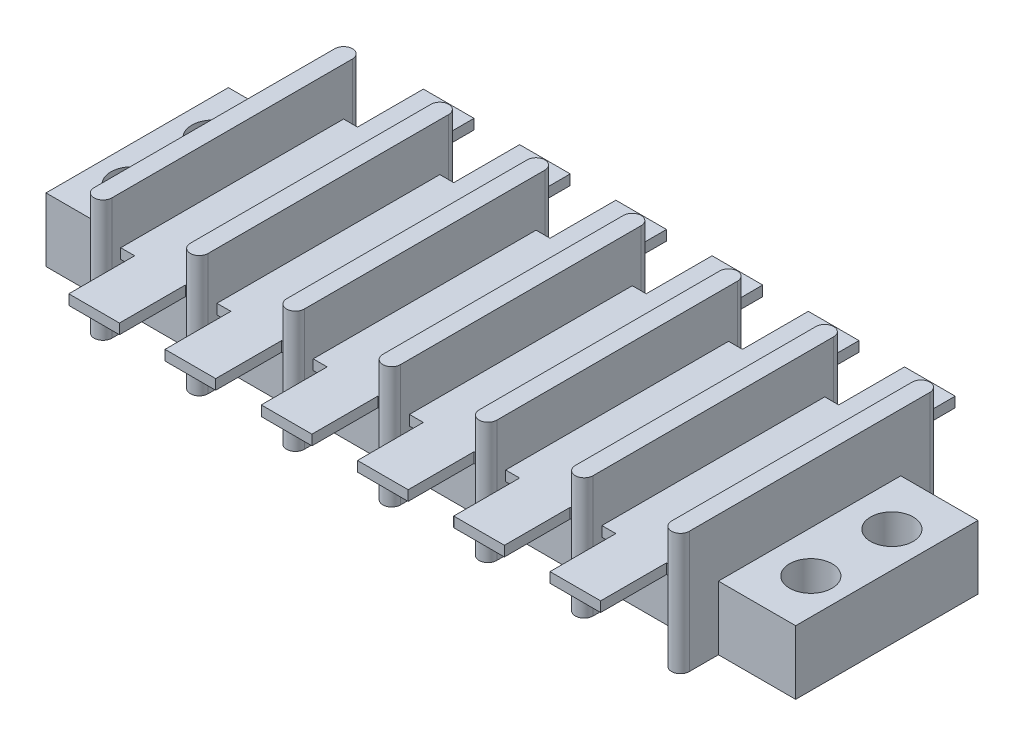
SolidWorks part; units mm, degrees
ref_plane "Front Plane" through (0, 0, 0) normal (0, 0, 1) x (1, 0, 0)
ref_plane "Top Plane" through (0, 0, 0) normal (0, 1, 0) x (1, 0, 0)
ref_plane "Right Plane" through (0, 0, 0) normal (1, 0, 0) x (0, 0, -1)
sketch "Sketch1" plane through (0, 0, 0) normal (0, 1, 0) x (1, 0, 0)
  line L1 (-37, -9) -> (37, -9)
  line L2 (-37, -9) -> (-37, 9)
  line L3 (-37, 9) -> (37, 9)
  line L4 (37, -9) -> (37, 9)
  line L5 (-37, -9) -> (37, 9) construction
  line L6 (-37, 9) -> (37, -9) construction
  point P0 (0, 0)
  dimension "D1" = 74
  dimension "D2" = 18
extrude "Boss-Extrude1" add sketch "Sketch1" along normal blind 6.3
sketch "Sketch4" plane through (0, 0, 0) normal (0, 1, 0) x (1, 0, 0)
  line L0 (-28.5, 11.875) -> (-28.5, -11.875) construction
  line L1 (-27.625, 11.875) -> (-27.625, -11.875)
  line L2 (-29.375, 11.875) -> (-29.375, -11.875)
  line L3 (-37, 9) -> (-37, -9) construction
  line L4 (-19, 11.875) -> (-19, -11.875) construction
  line L7 (-18.125, 11.875) -> (-18.125, -11.875)
  line L10 (-19.875, 11.875) -> (-19.875, -11.875)
  line L13 (-9.5, 11.875) -> (-9.5, -11.875) construction
  line L16 (-8.625, 11.875) -> (-8.625, -11.875)
  line L19 (-10.375, 11.875) -> (-10.375, -11.875)
  line L22 (0, 11.875) -> (0, -11.875) construction
  line L23 (0.875, 11.875) -> (0.875, -11.875)
  line L24 (-0.875, 11.875) -> (-0.875, -11.875)
  line L25 (9.5, 11.875) -> (9.5, -11.875) construction
  line L26 (10.375, 11.875) -> (10.375, -11.875)
  line L27 (8.625, 11.875) -> (8.625, -11.875)
  line L28 (19, 11.875) -> (19, -11.875) construction
  line L29 (19.875, 11.875) -> (19.875, -11.875)
  line L30 (18.125, 11.875) -> (18.125, -11.875)
  line L31 (28.5, 11.875) -> (28.5, -11.875) construction
  line L32 (29.375, 11.875) -> (29.375, -11.875)
  line L33 (27.625, 11.875) -> (27.625, -11.875)
  arc A0 (-27.625, 11.875) -> (-29.375, 11.875) centre (-28.5, 11.875) ccw
  arc A1 (-29.375, -11.875) -> (-27.625, -11.875) centre (-28.5, -11.875) ccw
  arc A14 (-18.125, 11.875) -> (-19.875, 11.875) centre (-19, 11.875) ccw
  arc A15 (-19.875, -11.875) -> (-18.125, -11.875) centre (-19, -11.875) ccw
  arc A16 (-8.625, 11.875) -> (-10.375, 11.875) centre (-9.5, 11.875) ccw
  arc A17 (-10.375, -11.875) -> (-8.625, -11.875) centre (-9.5, -11.875) ccw
  arc A18 (0.875, 11.875) -> (-0.875, 11.875) centre (0, 11.875) ccw
  arc A19 (-0.875, -11.875) -> (0.875, -11.875) centre (0, -11.875) ccw
  arc A20 (10.375, 11.875) -> (8.625, 11.875) centre (9.5, 11.875) ccw
  arc A21 (8.625, -11.875) -> (10.375, -11.875) centre (9.5, -11.875) ccw
  arc A22 (19.875, 11.875) -> (18.125, 11.875) centre (19, 11.875) ccw
  arc A23 (18.125, -11.875) -> (19.875, -11.875) centre (19, -11.875) ccw
  arc A24 (29.375, 11.875) -> (27.625, 11.875) centre (28.5, 11.875) ccw
  arc A25 (27.625, -11.875) -> (29.375, -11.875) centre (28.5, -11.875) ccw
  point P2 (-28.5, 0)
  point P10 (-37, 0)
  point P11 (-28.5, 11)
  point P12 (-28.5, -11)
  point P15 (-19, 0)
  point P20 (-19, 11)
  point P21 (-19, -11)
  point P25 (-9.5, 0)
  point P30 (-9.5, 11)
  point P31 (-9.5, -11)
  point P34 (0, 0)
  point P39 (0, 11)
  point P40 (0, -11)
  point P44 (9.5, 0)
  point P49 (9.5, 11)
  point P50 (9.5, -11)
  point P53 (19, 0)
  point P58 (19, 11)
  point P59 (19, -11)
  point P62 (28.5, 0)
  point P68 (28.5, 11)
  point P69 (28.5, -11)
  dimension "D1" = 22
  dimension "D2" = 1.75
  dimension "D3" = 22
  dimension "D4" = 1.75
  dimension "D5" = 22
  dimension "D6" = 1.75
  dimension "D7" = 22
  dimension "D8" = 1.75
  dimension "D9" = 22
  dimension "D10" = 1.75
  dimension "D11" = 22
  dimension "D12" = 1.75
  dimension "D13" = 22
  dimension "D14" = 1.75
  dimension "D15" = 8.5
  dimension "D16" = 9.5
  dimension "D17" = 9.5
  dimension "D18" = 9.5
  dimension "D19" = 9.5
  dimension "D20" = 9.5
  dimension "D21" = 9.5
extrude "Boss-Extrude2" add sketch "Sketch4" along normal blind 12
sketch "Sketch5" plane through (0, 6.3, 0) normal (0, 1, 0) x (1, 0, 0)
  line L0 (-37, 9) -> (-37, -9) construction
  line L1 (-27.625, 11) -> (-26.25, 11)
  line L2 (-27.625, 11) -> (-27.625, -11)
  line L3 (-27.625, -11) -> (-26.25, -11)
  line L4 (-19.875, 11) -> (-19.875, -11)
  line L5 (-27.625, 11) -> (-19.875, -11) construction
  line L6 (-27.625, -11) -> (-19.875, 11) construction
  line L7 (-27.625, -11.875) -> (-27.625, 11.875) construction
  line L8 (-21.25, 11) -> (-19.875, 11)
  line L9 (-26.25, 17.5) -> (-21.25, 17.5)
  line L10 (-26.25, 17.5) -> (-26.25, 11)
  line L11 (-26.25, -17.5) -> (-21.25, -17.5)
  line L12 (-21.25, 17.5) -> (-21.25, 11)
  line L13 (-26.25, 17.5) -> (-21.25, -17.5) construction
  line L14 (-26.25, -17.5) -> (-21.25, 17.5) construction
  line L15 (-26.25, -11) -> (-26.25, -17.5)
  line L16 (-21.25, -11) -> (-21.25, -17.5)
  line L17 (-21.25, -11) -> (-19.875, -11)
  line L18 (-18.125, 11) -> (-16.75, 11)
  line L19 (-18.125, 11) -> (-18.125, -11)
  line L20 (-18.125, -11) -> (-16.75, -11)
  line L21 (-10.375, 11) -> (-10.375, -11)
  line L22 (-18.125, 11) -> (-10.375, -11) construction
  line L23 (-18.125, -11) -> (-10.375, 11) construction
  line L24 (-11.75, 11) -> (-10.375, 11)
  line L25 (-16.75, 17.5) -> (-11.75, 17.5)
  line L26 (-16.75, 17.5) -> (-16.75, 11)
  line L27 (-16.75, -17.5) -> (-11.75, -17.5)
  line L28 (-11.75, 17.5) -> (-11.75, 11)
  line L29 (-16.75, 17.5) -> (-11.75, -17.5) construction
  line L30 (-16.75, -17.5) -> (-11.75, 17.5) construction
  line L31 (-16.75, -11) -> (-16.75, -17.5)
  line L32 (-11.75, -11) -> (-11.75, -17.5)
  line L33 (-11.75, -11) -> (-10.375, -11)
  line L34 (-18.125, -11.875) -> (-18.125, 11.875) construction
  line L35 (-8.625, 11) -> (-7.25, 11)
  line L36 (-8.625, 11) -> (-8.625, -11)
  line L37 (-8.625, -11) -> (-7.25, -11)
  line L38 (-0.875, 11) -> (-0.875, -11)
  line L39 (-8.625, 11) -> (-0.875, -11) construction
  line L40 (-8.625, -11) -> (-0.875, 11) construction
  line L41 (-2.25, 11) -> (-0.875, 11)
  line L42 (-7.25, 17.5) -> (-2.25, 17.5)
  line L43 (-7.25, 17.5) -> (-7.25, 11)
  line L44 (-7.25, -17.5) -> (-2.25, -17.5)
  line L45 (-2.25, 17.5) -> (-2.25, 11)
  line L46 (-7.25, 17.5) -> (-2.25, -17.5) construction
  line L47 (-7.25, -17.5) -> (-2.25, 17.5) construction
  line L48 (-7.25, -11) -> (-7.25, -17.5)
  line L49 (-2.25, -11) -> (-2.25, -17.5)
  line L50 (-2.25, -11) -> (-0.875, -11)
  line L51 (-10.375, 11.875) -> (-10.375, -11.875) construction
  line L52 (-8.625, -11.875) -> (-8.625, 11.875) construction
  line L53 (-0.875, 11.875) -> (-0.875, -11.875) construction
  line L54 (0.875, 11) -> (2.25, 11)
  line L55 (0.875, 11) -> (0.875, -11)
  line L56 (0.875, -11) -> (2.25, -11)
  line L57 (8.625, 11) -> (8.625, -11)
  line L58 (0.875, 11) -> (8.625, -11) construction
  line L59 (0.875, -11) -> (8.625, 11) construction
  line L60 (7.25, 11) -> (8.625, 11)
  line L61 (2.25, 17.5) -> (7.25, 17.5)
  line L62 (2.25, 17.5) -> (2.25, 11)
  line L63 (2.25, -17.5) -> (7.25, -17.5)
  line L64 (7.25, 17.5) -> (7.25, 11)
  line L65 (2.25, 17.5) -> (7.25, -17.5) construction
  line L66 (2.25, -17.5) -> (7.25, 17.5) construction
  line L67 (2.25, -11) -> (2.25, -17.5)
  line L68 (7.25, -11) -> (7.25, -17.5)
  line L69 (7.25, -11) -> (8.625, -11)
  line L70 (10.375, 11) -> (11.75, 11)
  line L71 (10.375, 11) -> (10.375, -11)
  line L72 (10.375, -11) -> (11.75, -11)
  line L73 (18.125, 11) -> (18.125, -11)
  line L74 (10.375, 11) -> (18.125, -11) construction
  line L75 (10.375, -11) -> (18.125, 11) construction
  line L76 (16.75, 11) -> (18.125, 11)
  line L77 (11.75, 17.5) -> (16.75, 17.5)
  line L78 (11.75, 17.5) -> (11.75, 11)
  line L79 (11.75, -17.5) -> (16.75, -17.5)
  line L80 (16.75, 17.5) -> (16.75, 11)
  line L81 (11.75, 17.5) -> (16.75, -17.5) construction
  line L82 (11.75, -17.5) -> (16.75, 17.5) construction
  line L83 (11.75, -11) -> (11.75, -17.5)
  line L84 (16.75, -11) -> (16.75, -17.5)
  line L85 (16.75, -11) -> (18.125, -11)
  line L86 (19.875, 11) -> (21.25, 11)
  line L87 (19.875, 11) -> (19.875, -11)
  line L88 (19.875, -11) -> (21.25, -11)
  line L89 (27.625, 11) -> (27.625, -11)
  line L90 (19.875, 11) -> (27.625, -11) construction
  line L91 (19.875, -11) -> (27.625, 11) construction
  line L92 (26.25, 11) -> (27.625, 11)
  line L93 (21.25, 17.5) -> (26.25, 17.5)
  line L94 (21.25, 17.5) -> (21.25, 11)
  line L95 (21.25, -17.5) -> (26.25, -17.5)
  line L96 (26.25, 17.5) -> (26.25, 11)
  line L97 (21.25, 17.5) -> (26.25, -17.5) construction
  line L98 (21.25, -17.5) -> (26.25, 17.5) construction
  line L99 (21.25, -11) -> (21.25, -17.5)
  line L100 (26.25, -11) -> (26.25, -17.5)
  line L101 (26.25, -11) -> (27.625, -11)
  line L102 (0.875, -9) -> (0.875, 9) construction
  line L103 (10.375, -9) -> (10.375, 9) construction
  line L104 (19.875, -9) -> (19.875, 9) construction
  line L105 (18.125, 11.875) -> (18.125, -11.875) construction
  line L106 (27.625, 11.875) -> (27.625, -11.875) construction
  point P0 (-23.75, 0)
  point P5 (-14.25, 0)
  point P8 (-37, 0)
  point P11 (-23.75, 0)
  point P26 (-14.25, 0)
  point P40 (-4.75, 0)
  point P45 (-4.75, 0)
  point P64 (4.75, 0)
  point P69 (14.25, 0)
  point P70 (4.75, 0)
  point P85 (14.25, 0)
  point P96 (23.75, 0)
  point P101 (23.75, 0)
  dimension "D1" = 7.75
  dimension "D2" = 22
  dimension "D3" = 5
  dimension "D4" = 35
  dimension "D5" = 22
  dimension "D6" = 5
  dimension "D7" = 35
  dimension "D8" = 22
  dimension "D9" = 5
  dimension "D10" = 35
  dimension "D11" = 7.75
  dimension "D12" = 22
  dimension "D13" = 5
  dimension "D14" = 35
  dimension "D15" = 22
  dimension "D16" = 5
  dimension "D17" = 35
  dimension "D18" = 22
  dimension "D19" = 5
  dimension "D20" = 35
extrude "Boss-Extrude3" add sketch "Sketch5" along normal blind 1
sketch "Sketch6" plane through (0, 6.3, 0) normal (0, 1, 0) x (1, 0, 0)
  line L0 (-29.375, 9) -> (-37, 9) construction
  line L1 (-37, -9) -> (-29.375, -9) construction
  line L2 (-37, 9) -> (-37, -9) construction
  line L3 (37, -9) -> (37, 9) construction
  circle A0 centre (-33.5, 4) radius 2.1
  circle A1 centre (-33.5, -4) radius 2.1
  circle A2 centre (33.5, 4) radius 2.1
  circle A3 centre (33.5, -4) radius 2.1
  dimension "D1" = 4.2
  dimension "D2" = 4.2
  dimension "D3" = 4.2
  dimension "D4" = 4.2
  dimension "D5" = 5
  dimension "D6" = 5
  dimension "D7" = 3.5
  dimension "D8" = 3.5
extrude "Cut-Extrude1" cut sketch "Sketch6" against normal through all
